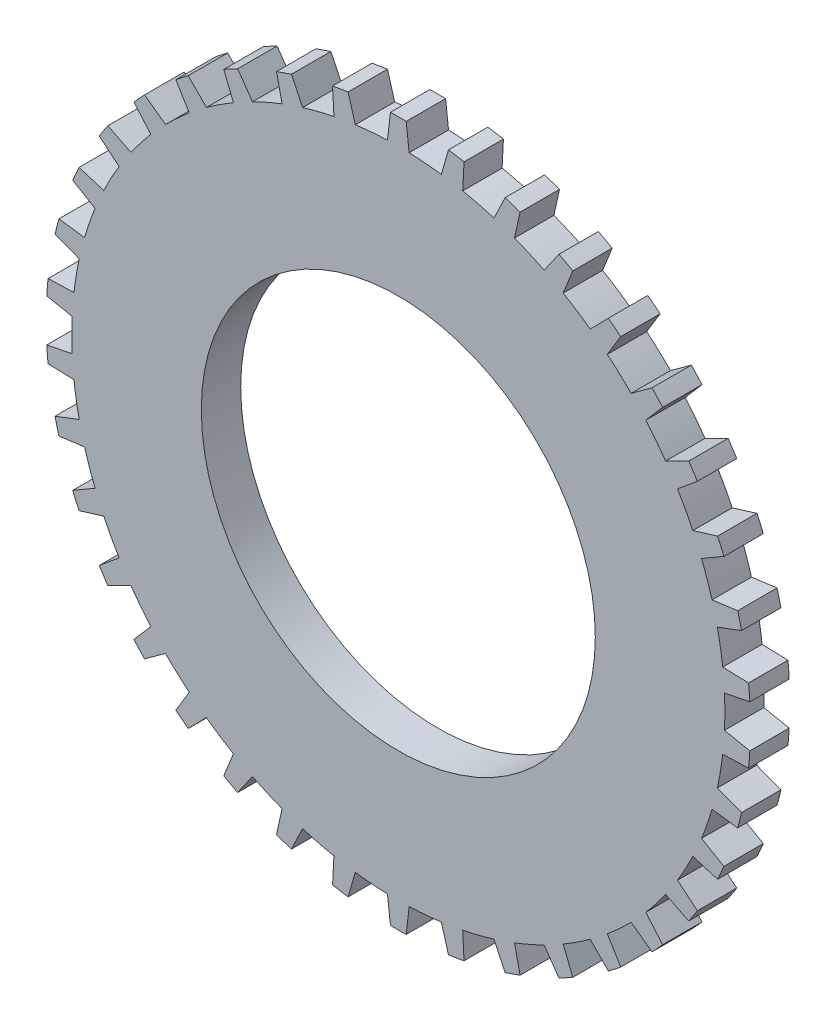
SolidWorks part; units mm, degrees
material "ABS"
ref_plane "Alzado" through (0, 0, 0) normal (0, 0, 1) x (1, 0, 0)
ref_plane "Planta" through (0, 0, 0) normal (0, 1, 0) x (1, 0, 0)
ref_plane "Vista lateral" through (0, 0, 0) normal (1, 0, 0) x (0, 0, -1)
sketch "Croquis1" plane through (0, 0, 0) normal (0, 0, 1) x (1, 0, 0)
  line L0 (0, 0) -> (0, 14.5885) construction
  line L1 (-0.4, 17.872) -> (-0.55, 16.5674)
  line L2 (0.4, 17.872) -> (0.55, 16.5674)
  line L3 (3.3362, 17.5624) -> (3.2694, 16.2509)
  line L4 (2.5471, 17.6941) -> (2.1844, 16.4319)
  line L5 (6.1814, 16.7738) -> (5.8996, 15.4911)
  line L6 (5.4247, 17.0335) -> (4.8592, 15.8483)
  line L7 (8.8579, 15.5276) -> (8.3689, 14.3088)
  line L8 (8.1543, 15.9083) -> (7.4015, 14.8323)
  line L9 (11.2929, 13.8578) -> (10.6099, 12.7362)
  line L10 (10.6616, 14.3492) -> (9.7419, 13.4118)
  line L11 (13.4198, 11.8101) -> (12.5615, 10.8161)
  line L12 (12.878, 12.3987) -> (11.8165, 11.6254)
  line L13 (15.1806, 9.4402) -> (14.1705, 8.601)
  line L14 (14.7431, 10.1099) -> (13.5688, 9.5219)
  line L15 (16.5274, 6.8128) -> (15.3929, 6.1514)
  line L16 (16.206, 7.5454) -> (14.951, 7.1587)
  line L17 (17.4233, 3.9996) -> (16.1954, 3.5339)
  line L18 (17.2269, 4.7751) -> (15.9254, 4.6002)
  line L19 (17.844, 1.0772) -> (16.5562, 0.82)
  line L20 (17.7779, 1.8745) -> (16.4654, 1.9162)
  line L21 (17.7779, -1.8745) -> (16.4654, -1.9162)
  line L22 (17.844, -1.0772) -> (16.5562, -0.82)
  line L23 (17.2269, -4.7751) -> (15.9254, -4.6002)
  line L24 (17.4233, -3.9996) -> (16.1954, -3.5339)
  line L25 (16.206, -7.5454) -> (14.951, -7.1587)
  line L26 (16.5274, -6.8128) -> (15.3929, -6.1514)
  line L27 (14.7431, -10.1099) -> (13.5688, -9.5219)
  line L28 (15.1806, -9.4402) -> (14.1705, -8.601)
  line L29 (12.878, -12.3987) -> (11.8165, -11.6254)
  line L30 (13.4198, -11.8101) -> (12.5615, -10.8161)
  line L31 (10.6616, -14.3492) -> (9.7419, -13.4118)
  line L32 (11.2929, -13.8578) -> (10.6099, -12.7362)
  line L33 (8.1543, -15.9083) -> (7.4015, -14.8323)
  line L34 (8.8579, -15.5276) -> (8.3689, -14.3088)
  line L35 (5.4247, -17.0335) -> (4.8592, -15.8483)
  line L36 (6.1814, -16.7738) -> (5.8996, -15.4911)
  line L37 (2.5471, -17.6941) -> (2.1844, -16.4319)
  line L38 (3.3362, -17.5624) -> (3.2694, -16.2509)
  line L39 (-0.4, -17.872) -> (-0.55, -16.5674)
  line L40 (0.4, -17.872) -> (0.55, -16.5674)
  line L41 (-3.3362, -17.5624) -> (-3.2694, -16.2509)
  line L42 (-2.5471, -17.6941) -> (-2.1844, -16.4319)
  line L43 (-6.1814, -16.7738) -> (-5.8996, -15.4911)
  line L44 (-5.4247, -17.0335) -> (-4.8592, -15.8483)
  line L45 (-8.8579, -15.5276) -> (-8.3689, -14.3088)
  line L46 (-8.1543, -15.9083) -> (-7.4015, -14.8323)
  line L47 (-11.2929, -13.8578) -> (-10.6099, -12.7362)
  line L48 (-10.6616, -14.3492) -> (-9.7419, -13.4118)
  line L49 (-13.4198, -11.8101) -> (-12.5615, -10.8161)
  line L50 (-12.878, -12.3987) -> (-11.8165, -11.6254)
  line L51 (-15.1806, -9.4402) -> (-14.1705, -8.601)
  line L52 (-14.7431, -10.1099) -> (-13.5688, -9.5219)
  line L53 (-16.5274, -6.8128) -> (-15.3929, -6.1514)
  line L54 (-16.206, -7.5454) -> (-14.951, -7.1587)
  line L55 (-17.4233, -3.9996) -> (-16.1954, -3.5339)
  line L56 (-17.2269, -4.7751) -> (-15.9254, -4.6002)
  line L57 (-17.844, -1.0772) -> (-16.5562, -0.82)
  line L58 (-17.7779, -1.8745) -> (-16.4654, -1.9162)
  line L59 (-17.7779, 1.8745) -> (-16.4654, 1.9162)
  line L60 (-17.844, 1.0772) -> (-16.5562, 0.82)
  line L61 (-17.2269, 4.7751) -> (-15.9254, 4.6002)
  line L62 (-17.4233, 3.9996) -> (-16.1954, 3.5339)
  line L63 (-16.206, 7.5454) -> (-14.951, 7.1587)
  line L64 (-16.5274, 6.8128) -> (-15.3929, 6.1514)
  line L65 (-14.7431, 10.1099) -> (-13.5688, 9.5219)
  line L66 (-15.1806, 9.4402) -> (-14.1705, 8.601)
  line L67 (-12.878, 12.3987) -> (-11.8165, 11.6254)
  line L68 (-13.4198, 11.8101) -> (-12.5615, 10.8161)
  line L69 (-10.6616, 14.3492) -> (-9.7419, 13.4118)
  line L70 (-11.2929, 13.8578) -> (-10.6099, 12.7362)
  line L71 (-8.1543, 15.9083) -> (-7.4015, 14.8323)
  line L72 (-8.8579, 15.5276) -> (-8.3689, 14.3088)
  line L73 (-5.4247, 17.0335) -> (-4.8592, 15.8483)
  line L74 (-6.1814, 16.7738) -> (-5.8996, 15.4911)
  line L75 (-2.5471, 17.6941) -> (-2.1844, 16.4319)
  line L76 (-3.3362, 17.5624) -> (-3.2694, 16.2509)
  line L77 (-6.1814, 16.7738) -> (-5.4247, 17.0335)
  line L78 (-3.3362, 17.5624) -> (-2.5471, 17.6941)
  arc A0 (-14.7431, 10.1099) -> (-15.1806, 9.4402) centre (0, 0) ccw
  arc A1 (2.1844, 16.4319) -> (0.55, 16.5674) centre (0, 0) ccw
  arc A2 (-16.206, 7.5454) -> (-16.5274, 6.8128) centre (0, 0) ccw
  arc A3 (-17.2269, 4.7751) -> (-17.4233, 3.9996) centre (0, 0) ccw
  arc A4 (-17.7779, 1.8745) -> (-17.844, 1.0772) centre (0, 0) ccw
  arc A5 (-17.844, -1.0772) -> (-17.7779, -1.8745) centre (0, 0) ccw
  arc A6 (-17.4233, -3.9996) -> (-17.2269, -4.7751) centre (0, 0) ccw
  arc A7 (-16.5274, -6.8128) -> (-16.206, -7.5454) centre (0, 0) ccw
  arc A8 (-15.1806, -9.4402) -> (-14.7431, -10.1099) centre (0, 0) ccw
  arc A9 (-13.4198, -11.8101) -> (-12.878, -12.3987) centre (0, 0) ccw
  arc A10 (-11.2929, -13.8578) -> (-10.6616, -14.3492) centre (0, 0) ccw
  arc A11 (3.3362, 17.5624) -> (2.5471, 17.6941) centre (0, 0) ccw
  arc A12 (0.4, 17.872) -> (-0.4, 17.872) centre (0, 0) ccw
  arc A13 (-10.6616, 14.3492) -> (-11.2929, 13.8578) centre (0, 0) ccw
  arc A14 (-12.878, 12.3987) -> (-13.4198, 11.8101) centre (0, 0) ccw
  arc A15 (-8.1543, 15.9083) -> (-8.8579, 15.5276) centre (0, 0) ccw
  arc A16 (6.1814, 16.7738) -> (5.4247, 17.0335) centre (0, 0) ccw
  arc A17 (8.8579, 15.5276) -> (8.1543, 15.9083) centre (0, 0) ccw
  arc A18 (11.2929, 13.8578) -> (10.6616, 14.3492) centre (0, 0) ccw
  arc A19 (13.4198, 11.8101) -> (12.878, 12.3987) centre (0, 0) ccw
  arc A20 (15.1806, 9.4402) -> (14.7431, 10.1099) centre (0, 0) ccw
  arc A21 (16.5274, 6.8128) -> (16.206, 7.5454) centre (0, 0) ccw
  arc A22 (17.4233, 3.9996) -> (17.2269, 4.7751) centre (0, 0) ccw
  arc A23 (17.844, 1.0772) -> (17.7779, 1.8745) centre (0, 0) ccw
  arc A24 (17.7779, -1.8745) -> (17.844, -1.0772) centre (0, 0) ccw
  arc A25 (17.2269, -4.7751) -> (17.4233, -3.9996) centre (0, 0) ccw
  arc A26 (10.6616, -14.3492) -> (11.2929, -13.8578) centre (0, 0) ccw
  arc A27 (8.1543, -15.9083) -> (8.8579, -15.5276) centre (0, 0) ccw
  arc A28 (5.4247, -17.0335) -> (6.1814, -16.7738) centre (0, 0) ccw
  arc A29 (-0.4, -17.872) -> (0.4, -17.872) centre (0, 0) ccw
  arc A30 (-3.3362, -17.5624) -> (-2.5471, -17.6941) centre (0, 0) ccw
  arc A31 (-6.1814, -16.7738) -> (-5.4247, -17.0335) centre (0, 0) ccw
  arc A32 (-8.8579, -15.5276) -> (-8.1543, -15.9083) centre (0, 0) ccw
  arc A33 (12.878, -12.3987) -> (13.4198, -11.8101) centre (0, 0) ccw
  arc A34 (14.7431, -10.1099) -> (15.1806, -9.4402) centre (0, 0) ccw
  arc A35 (16.206, -7.5454) -> (16.5274, -6.8128) centre (0, 0) ccw
  arc A36 (4.8592, 15.8483) -> (3.2694, 16.2509) centre (0, 0) ccw
  arc A37 (7.4015, 14.8323) -> (5.8996, 15.4911) centre (0, 0) ccw
  arc A38 (-8.3689, 14.3088) -> (-9.7419, 13.4118) centre (0, 0) ccw
  arc A39 (-0.55, 16.5674) -> (-2.1844, 16.4319) centre (0, 0) ccw
  arc A40 (-10.6099, 12.7362) -> (-11.8165, 11.6254) centre (0, 0) ccw
  arc A41 (-12.5615, 10.8161) -> (-13.5688, 9.5219) centre (0, 0) ccw
  arc A42 (-14.1705, 8.601) -> (-14.951, 7.1587) centre (0, 0) ccw
  arc A43 (9.7419, 13.4118) -> (8.3689, 14.3088) centre (0, 0) ccw
  arc A44 (11.8165, 11.6254) -> (10.6099, 12.7362) centre (0, 0) ccw
  arc A45 (13.5688, 9.5219) -> (12.5615, 10.8161) centre (0, 0) ccw
  arc A46 (14.951, 7.1587) -> (14.1705, 8.601) centre (0, 0) ccw
  arc A47 (15.9254, 4.6002) -> (15.3929, 6.1514) centre (0, 0) ccw
  arc A48 (16.4654, 1.9162) -> (16.1954, 3.5339) centre (0, 0) ccw
  arc A49 (16.5562, -0.82) -> (16.5562, 0.82) centre (0, 0) ccw
  arc A50 (16.1954, -3.5339) -> (16.4654, -1.9162) centre (0, 0) ccw
  arc A51 (15.3929, -6.1514) -> (15.9254, -4.6002) centre (0, 0) ccw
  arc A52 (14.1705, -8.601) -> (14.951, -7.1587) centre (0, 0) ccw
  arc A53 (12.5615, -10.8161) -> (13.5688, -9.5219) centre (0, 0) ccw
  arc A54 (10.6099, -12.7362) -> (11.8165, -11.6254) centre (0, 0) ccw
  arc A55 (8.3689, -14.3088) -> (9.7419, -13.4118) centre (0, 0) ccw
  arc A56 (5.8996, -15.4911) -> (7.4015, -14.8323) centre (0, 0) ccw
  arc A57 (3.2694, -16.2509) -> (4.8592, -15.8483) centre (0, 0) ccw
  arc A58 (0.55, -16.5674) -> (2.1844, -16.4319) centre (0, 0) ccw
  arc A59 (-2.1844, -16.4319) -> (-0.55, -16.5674) centre (0, 0) ccw
  arc A60 (-4.8592, -15.8483) -> (-3.2694, -16.2509) centre (0, 0) ccw
  arc A61 (-7.4015, -14.8323) -> (-5.8996, -15.4911) centre (0, 0) ccw
  arc A62 (-9.7419, -13.4118) -> (-8.3689, -14.3088) centre (0, 0) ccw
  arc A63 (-11.8165, -11.6254) -> (-10.6099, -12.7362) centre (0, 0) ccw
  arc A64 (-13.5688, -9.5219) -> (-12.5615, -10.8161) centre (0, 0) ccw
  arc A65 (-14.951, -7.1587) -> (-14.1705, -8.601) centre (0, 0) ccw
  arc A66 (-15.9254, -4.6002) -> (-15.3929, -6.1514) centre (0, 0) ccw
  arc A67 (-16.4654, -1.9162) -> (-16.1954, -3.5339) centre (0, 0) ccw
  arc A68 (-16.5562, 0.82) -> (-16.5562, -0.82) centre (0, 0) ccw
  arc A69 (-16.1954, 3.5339) -> (-16.4654, 1.9162) centre (0, 0) ccw
  arc A70 (-15.3929, 6.1514) -> (-15.9254, 4.6002) centre (0, 0) ccw
  arc A71 (2.5471, -17.6941) -> (3.3362, -17.5624) centre (0, 0) ccw
  circle A72 centre (0, 0) radius 10
  arc A73 (-5.8996, 15.4911) -> (-7.4015, 14.8323) centre (0, 0) ccw
  arc A74 (-3.2694, 16.2509) -> (-4.8592, 15.8483) centre (0, 0) ccw
  point P151 (0, 0)
  dimension "D1" = 1.3
  dimension "D6" = 20
  dimension "D2" = 1.1
  dimension "D3" = 0.8
  dimension "D5" = 1.64
  dimension "D4" = 38
extrude "Saliente-Extruir1" add sketch "Croquis1" along normal blind 2
